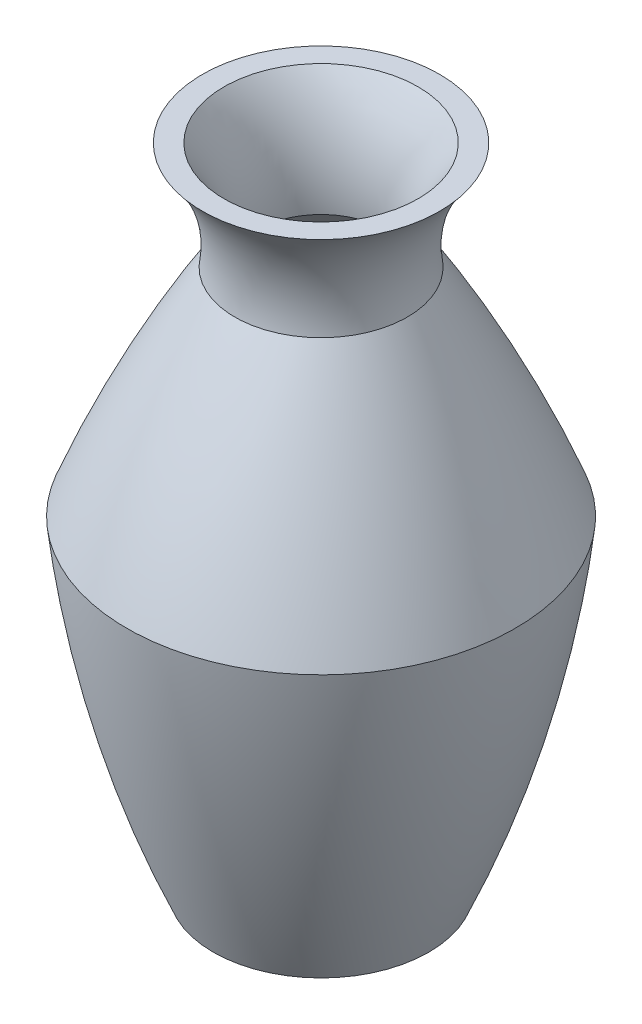
SolidWorks part; units mm, degrees
ref_plane "前视基准面" through (0, 0, 0) normal (0, 0, 1) x (1, 0, 0)
ref_plane "上视基准面" through (0, 0, 0) normal (0, 1, 0) x (1, 0, 0)
ref_plane "右视基准面" through (0, 0, 0) normal (1, 0, 0) x (0, 0, -1)
sketch "草图1" plane through (0, 0, 0) normal (0, 0, 1) x (1, 0, 0)
  line L0 (0, 0) -> (0, 150) construction
  line L1 (0, 0) -> (25, 0)
  line L2 (27.5, 150) -> (0, 150)
  line L3 (0, 150) -> (0, 0)
  arc A0 (25, 0) -> (45, 75) centre (-214.5417, 104.0444) ccw
  arc A1 (45, 75) -> (20, 125) centre (-227.1667, -29.8333) ccw
  arc A2 (20, 125) -> (27.5, 150) centre (50.25, 129.55) cw
revolve "旋转1" add sketch "草图1" angle 360 about L0
sketch "草图2" plane through (0, 0, 0) normal (0, 0, 1) x (1, 0, 0)
  line L0 (0, 0) -> (0, 150) construction
  line L1 (0, 10) -> (26, 10)
  line L2 (22.5, 150) -> (0, 150)
  line L3 (0, 150) -> (0, 10)
  arc A0 (26, 10) -> (40, 75) centre (-143.3366, 80.4802) ccw
  arc A1 (40, 75) -> (15, 125) centre (-47.5, 62.5) ccw
  arc A2 (15, 125) -> (22.5, 150) centre (50.95, 127.84) cw
revolve "切除-旋转1" cut sketch "草图2" angle 360 about L0
